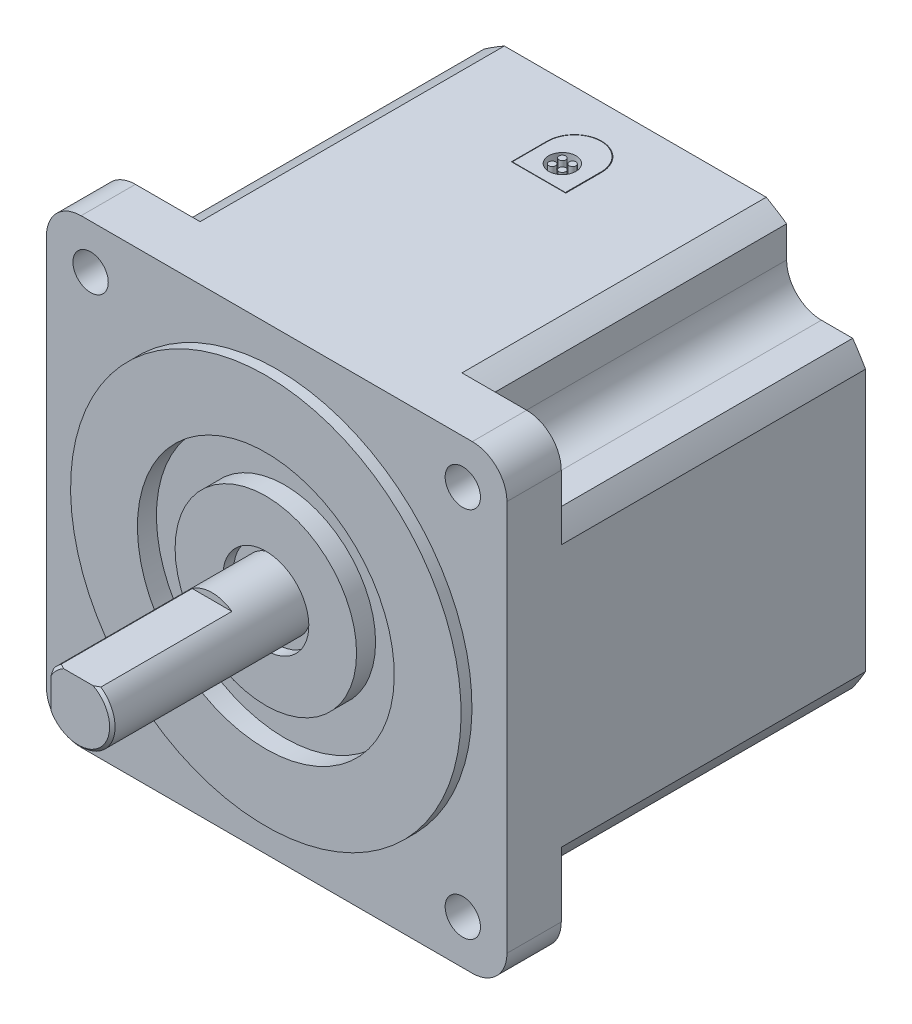
SolidWorks part; units mm, degrees
ref_plane "Front Plane" through (0, 0, 0) normal (0, 0, 1) x (1, 0, 0)
ref_plane "Top Plane" through (0, 0, 0) normal (0, 1, 0) x (1, 0, 0)
ref_plane "Right Plane" through (0, 0, 0) normal (1, 0, 0) x (0, 0, -1)
sketch "Sketch1" plane through (0, 0, 0) normal (0, 0, 1) x (1, 0, 0)
  line L0 (-5.1562, -3.7062) -> (-5.1562, 3.7062) construction
  line L1 (43.053, -43.053) -> (-43.053, -43.053) construction
  line L2 (43.053, -43.053) -> (43.053, 43.053) construction
  line L3 (43.053, 43.053) -> (-43.053, 43.053) construction
  line L4 (-43.053, -43.053) -> (-43.053, 43.053) construction
  line L5 (43.053, -43.053) -> (-43.053, 43.053) construction
  line L6 (43.053, 43.053) -> (-43.053, -43.053) construction
  line L7 (34.798, -34.798) -> (-34.798, -34.798) construction
  line L8 (34.798, -34.798) -> (34.798, 34.798) construction
  line L9 (34.798, 34.798) -> (-34.798, 34.798) construction
  line L10 (-34.798, -34.798) -> (-34.798, 34.798) construction
  line L11 (34.798, -34.798) -> (-34.798, 34.798) construction
  line L12 (34.798, 34.798) -> (-34.798, -34.798) construction
  line L13 (-3.7062, 5.1562) -> (3.7062, 5.1562) construction
  circle A0 centre (-34.798, 34.798) radius 3.302 construction
  circle A1 centre (34.798, 34.798) radius 3.302 construction
  circle A2 centre (-34.798, -34.798) radius 3.302 construction
  circle A3 centre (34.798, -34.798) radius 3.302 construction
  circle A4 centre (0, 0) radius 6.35 construction
  circle A5 centre (0, 0) radius 36.5125 construction
  point P0 (0, 0)
  point P6 (0, 0)
  point P18 (0, 6.35)
  point P19 (0, 43.053)
  point P20 (0, 36.5125)
  point P21 (-34.798, -38.1)
  dimension "D3" = 6.604
  dimension "D4" = 12.7
  dimension "D5" = 73.025
  dimension "D1" = 86.106
  dimension "D2" = 69.596
  dimension "D6" = 11.5062
sketch "Sketch2" plane through (0, 0, 0) normal (1, 0, 0) x (0, 0, -1)
  line L0 (0, 0) -> (67.056, 0) construction
  line L1 (0, 0) -> (-37.084, 0) construction
  line L2 (-37.084, -6.35) -> (-37.084, 6.35) construction
  line L3 (67.056, -43.053) -> (67.056, 43.053) construction
  line L4 (0, 43.053) -> (0, -43.053) construction
  line L5 (-2.032, 36.5125) -> (-2.032, -36.5125) construction
  line L6 (10.16, 43.053) -> (10.16, -43.053) construction
  point P3 (-2.032, 0)
  point P18 (10.16, 0)
  point P19 (-12.0904, 0)
  dimension "D1" = 37.084
  dimension "A" = 67.056
  dimension "D2" = 2.032
  dimension "D3" = 10.16
  dimension "D4" = 24.9936
sketch "Sketch3" plane through (0, 0, 0) normal (0, 0, 1) x (1, 0, 0)
  line L1 (-43.053, -43.053) -> (-43.053, 43.053) construction
  line L2 (43.053, 43.053) -> (-43.053, 43.053) construction
  line L3 (43.053, -43.053) -> (43.053, 43.053) construction
  line L4 (43.053, -43.053) -> (-43.053, -43.053) construction
  line L5 (-43.053, -36.576) -> (-43.053, 36.576)
  line L6 (36.576, 43.053) -> (-36.576, 43.053)
  line L7 (43.053, -36.576) -> (43.053, 36.576)
  line L8 (36.576, -43.053) -> (-36.576, -43.053)
  arc A4 (-43.053, 36.576) -> (-36.576, 43.053) centre (-36.576, 36.576) cw
  arc A5 (36.576, 43.053) -> (43.053, 36.576) centre (36.576, 36.576) cw
  arc A6 (43.053, -36.576) -> (36.576, -43.053) centre (36.576, -36.576) cw
  arc A7 (-36.576, -43.053) -> (-43.053, -36.576) centre (-36.576, -36.576) cw
  dimension "D1" = 6.477
extrude "Boss-Extrude1" add sketch "Sketch3" against normal up to vertex (10.16 mm away) up to point (0, 0, -10.16)
sketch "Sketch4" plane through (0, 0, -10.16) normal (0, 0, 1) x (1, 0, 0)
  line L0 (0, 43.053) -> (0, 0) construction
  line L1 (0, 0) -> (-43.053, 0) construction
  line L2 (-40.6519, 28.2956) -> (-34.798, 28.2956)
  line L3 (-28.2956, 34.798) -> (-28.2956, 40.6519)
  line L4 (-43.053, 36.576) -> (-43.053, -36.576)
  line L5 (36.576, 43.053) -> (-36.576, 43.053)
  line L6 (43.053, -36.576) -> (43.053, 36.576)
  line L7 (-36.576, -43.053) -> (36.576, -43.053)
  line L8 (-43.053, 24.488) -> (-43.053, -24.488)
  line L9 (24.488, 43.053) -> (-24.488, 43.053)
  line L10 (43.053, -24.488) -> (43.053, 24.488)
  line L14 (43.053, 43.053) -> (-43.053, 43.053) construction
  line L15 (28.2956, 34.798) -> (28.2956, 40.6519)
  line L16 (40.6519, 28.2956) -> (34.798, 28.2956)
  line L17 (40.6519, -28.2956) -> (34.798, -28.2956)
  line L18 (28.2956, -34.798) -> (28.2956, -40.6519)
  line L19 (24.488, -43.053) -> (-24.488, -43.053)
  line L20 (-28.2956, -34.798) -> (-28.2956, -40.6519)
  line L21 (-40.6519, -28.2956) -> (-34.798, -28.2956)
  arc A0 (-24.488, 43.053) -> (-28.2956, 40.6519) centre (0, 0) ccw
  arc A1 (-40.6519, 28.2956) -> (-43.053, 24.488) centre (0, 0) ccw
  arc A2 (-34.798, 28.2956) -> (-28.2956, 34.798) centre (-34.798, 34.798) ccw
  arc A3 (34.798, 28.2956) -> (28.2956, 34.798) centre (34.798, 34.798) cw
  arc A4 (-36.576, 43.053) -> (-43.053, 36.576) centre (-36.576, 36.576) ccw
  arc A5 (40.6519, 28.2956) -> (43.053, 24.488) centre (0, 0) cw
  arc A6 (43.053, 36.576) -> (36.576, 43.053) centre (36.576, 36.576) ccw
  arc A7 (24.488, 43.053) -> (28.2956, 40.6519) centre (0, 0) cw
  arc A8 (36.576, -43.053) -> (43.053, -36.576) centre (36.576, -36.576) ccw
  arc A9 (40.6519, -28.2956) -> (43.053, -24.488) centre (0, 0) ccw
  arc A10 (-43.053, -36.576) -> (-36.576, -43.053) centre (-36.576, -36.576) ccw
  arc A11 (24.488, -43.053) -> (28.2956, -40.6519) centre (0, 0) ccw
  arc A12 (-24.488, -43.053) -> (-28.2956, -40.6519) centre (0, 0) cw
  arc A13 (34.798, -28.2956) -> (28.2956, -34.798) centre (34.798, -34.798) ccw
  arc A14 (-34.798, -28.2956) -> (-28.2956, -34.798) centre (-34.798, -34.798) cw
  arc A15 (-40.6519, -28.2956) -> (-43.053, -24.488) centre (0, 0) cw
  dimension "D2" = 6.5024
  dimension "D3" = 49.53
  dimension "D1" = 0
extrude "Boss-Extrude2" add sketch "Sketch4" against normal up to vertex (56.896 mm away) up to point (0, 0, -67.056)
sketch "Sketch5" plane through (0, 0, 0) normal (1, 0, 0) x (0, 0, -1)
  line L1 (0, 0) -> (-2.032, 0)
  line L2 (0, 0) -> (0, 36.5125)
  line L3 (0, 36.5125) -> (-2.032, 36.5125)
  line L4 (-2.032, 0) -> (-2.032, 36.5125)
revolve "Revolve1" add sketch "Sketch5" angle 360 about L1
sketch "Sketch6" plane through (0, 0, 0) normal (1, 0, 0) x (0, 0, -1)
  line L0 (-37.084, 0) -> (-2.032, 0) construction
  line L1 (67.056, 0) -> (-2.032, 0)
  line L2 (67.056, 0) -> (67.056, 6.35)
  line L3 (0, 8.0391) -> (-2.032, 8.0391)
  line L4 (-2.032, 0) -> (-2.032, 8.0391)
  line L5 (67.056, 6.35) -> (0, 6.35)
  line L6 (0, 6.35) -> (0, 8.0391)
  line L7 (-2.032, 36.5125) -> (-2.032, -36.5125) construction
  line L10 (-2.032, 16.9672) -> (1.524, 16.9672)
  line L11 (-2.032, 16.9672) -> (-2.032, 24.0157)
  line L12 (-2.032, 24.0157) -> (1.524, 24.0157)
  line L13 (1.524, 16.9672) -> (1.524, 24.0157)
  dimension "D1" = 16.0782
  dimension "D2" = 33.9344
  dimension "D3" = 3.556
  dimension "D4" = 48.0314
revolve "Cut-Revolve1" cut sketch "Sketch6" angle 360 about L0
sketch "Sketch7" plane through (0, 0, 0) normal (1, 0, 0) x (0, 0, -1)
  line L1 (-37.084, 6.35) -> (67.056, 6.35)
  line L2 (-37.084, 6.35) -> (-37.084, 0)
  line L3 (-37.084, 0) -> (67.056, 0)
  line L4 (67.056, 6.35) -> (67.056, 0)
revolve "Revolve2" add sketch "Sketch7" angle 360 about L3
chamfer "Chamfer1" distance 0.508 angle 45 2 edges at (0, -6.35, -67.056) (0, -6.35, 37.084)
sketch "Sketch8" plane through (0, 0, 37.084) normal (0, 0, 1) x (1, 0, 0)
  line L0 (-5.1562, -3.7062) -> (-5.1562, 3.7062) construction
  line L1 (-5.1562, -3.7062) -> (-5.1562, 3.7062)
  line L2 (-3.7062, 5.1562) -> (3.7062, 5.1562) construction
  line L3 (-3.7062, 5.1562) -> (3.7062, 5.1562)
  circle A0 centre (0, 0) radius 6.35 construction
  arc A1 (3.7062, 5.1562) -> (-3.7062, 5.1562) centre (0, 0) ccw
  arc A2 (-5.1562, 3.7062) -> (-5.1562, -3.7062) centre (0, 0) ccw
extrude "Cut-Extrude1" cut sketch "Sketch8" against normal up to vertex (24.9936 mm away) up to point (0, 0, 12.0904)
sketch "Sketch9" plane through (0, 0, 0) normal (0, 0, 1) x (1, 0, 0)
  circle A0 centre (34.798, -34.798) radius 3.302 construction
  circle A1 centre (34.798, -34.798) radius 3.302
  circle A2 centre (-34.798, -34.798) radius 3.302 construction
  circle A3 centre (-34.798, 34.798) radius 3.302 construction
  circle A4 centre (34.798, 34.798) radius 3.302 construction
  circle A5 centre (-34.798, -34.798) radius 3.302
  circle A6 centre (-34.798, 34.798) radius 3.302
  circle A7 centre (34.798, 34.798) radius 3.302
extrude "Cut-Extrude2" cut sketch "Sketch9" against normal up to next (10.16 mm away)
sketch "Sketch10" plane through (0, 43.053, -0.7512) normal (0, 1, 0) x (1, 0, 0)
  line L0 (0, -0.7512) -> (0, 54.9256) construction
  line L2 (-5.08, 54.9256) -> (-5.08, 48.22)
  line L3 (-5.08, 48.22) -> (5.08, 48.22)
  line L4 (5.08, 54.9256) -> (5.08, 48.22)
  line L7 (24.488, 66.3048) -> (-24.488, 66.3048) construction
  arc A0 (5.08, 54.9256) -> (-5.08, 54.9256) centre (0, 54.9256) ccw
  dimension "D1" = 10.16
  dimension "D2" = 6.7056
  dimension "D3" = 11.3792
extrude "Cut-Extrude3" cut sketch "Sketch10" against normal blind 1.9431
sketch "Sketch11" plane through (0, 41.1099, 0) normal (0, 1, 0) x (1, 0, 0)
  line L0 (-4.9657, 55.6768) -> (-4.9657, 49.022)
  line L1 (4.9657, 55.6768) -> (4.9657, 49.022)
  line L2 (4.9657, 49.022) -> (-4.9657, 49.022)
  circle A0 centre (0, 53.4162) radius 2.54
  arc A1 (4.9657, 55.6768) -> (-4.9657, 55.6768) centre (0, 55.6768) ccw
  dimension "D1" = 4.3942
  dimension "D2" = 9.9314
  dimension "D3" = 5.08
  dimension "D4" = 2.2606
extrude "Boss-Extrude3" add sketch "Sketch11" along normal offset from surface (1.9685 mm away) 0.0254 up to face at (0, 43.053, -53.594) offset beyond the face yes
sketch "Sketch13" plane through (0, 41.1099, 0) normal (0, 1, 0) x (1, 0, 0)
  line L4 (-0.9525, 52.4637) -> (0.9525, 52.4637) construction
  line L5 (-0.9525, 52.4637) -> (-0.9525, 54.3687) construction
  line L6 (-0.9525, 54.3687) -> (0.9525, 54.3687) construction
  line L7 (0.9525, 52.4637) -> (0.9525, 54.3687) construction
  line L8 (-0.9525, 52.4637) -> (0.9525, 54.3687) construction
  line L9 (-0.9525, 54.3687) -> (0.9525, 52.4637) construction
  circle A0 centre (-0.9525, 54.3687) radius 0.635
  circle A1 centre (0.9525, 54.3687) radius 0.635
  circle A2 centre (0.9525, 52.4637) radius 0.635
  circle A3 centre (-0.9525, 52.4637) radius 0.635
  circle A5 centre (0, 53.4162) radius 2.54 construction
  point P8 (0, 53.4162)
  dimension "D1" = 1.27
  dimension "D2" = 1.905
extrude "Boss-Extrude4" add sketch "Sketch13" along normal blind 1.9304
